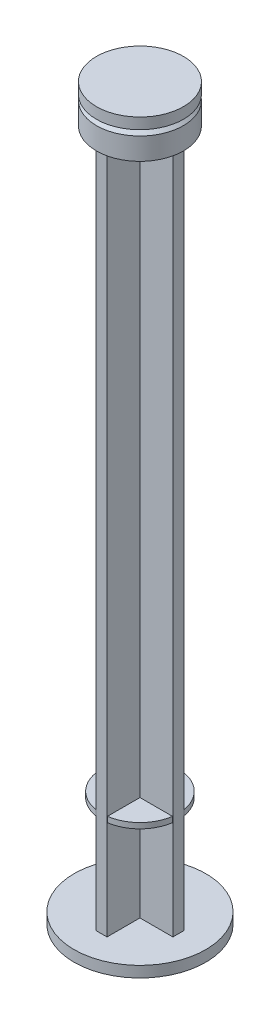
SolidWorks part; units mm, degrees
ref_plane "Front Plane" through (0, 0, 0) normal (0, 0, 1) x (1, 0, 0)
ref_plane "Top Plane" through (0, 0, 0) normal (0, 1, 0) x (1, 0, 0)
ref_plane "Right Plane" through (0, 0, 0) normal (1, 0, 0) x (0, 0, -1)
sketch "Sketch1" plane through (0, 0, 0) normal (0, 1, 0) x (1, 0, 0)
  circle A0 centre (0, 0) radius 6
  dimension "D1" = 12
extrude "Extrude1" add sketch "Sketch1" along normal blind 1
sketch "Sketch2" plane through (0, 1, 0) normal (0, 1, 0) x (-1, 0, 0)
  line L0 (0.5, 0.5) -> (0.5, 3.5)
  line L1 (-3.5, -0.5) -> (-0.5, -0.5)
  line L2 (-3.5, -0.5) -> (-3.5, 0.5)
  line L3 (-3.5, 0.5) -> (-0.5, 0.5)
  line L4 (3.5, -0.5) -> (3.5, 0.5)
  line L5 (-0.5, -3.5) -> (0.5, -3.5)
  line L6 (-0.5, -3.5) -> (-0.5, -0.5)
  line L7 (-0.5, 3.5) -> (0.5, 3.5)
  line L8 (0.5, -3.5) -> (0.5, -0.5)
  line L9 (0.5, 0.5) -> (3.5, 0.5)
  line L10 (-0.5, 0.5) -> (-0.5, 3.5)
  line L11 (0.5, -0.5) -> (3.5, -0.5)
  dimension "D1" = 0.5
  dimension "D2" = 0.5
  dimension "D3" = 3.5
  dimension "D4" = 3.5
  dimension "D5" = 0.5
  dimension "D6" = 0.5
  dimension "D7" = 3.5
  dimension "D8" = 3.5
extrude "Extrude2" add sketch "Sketch2" along normal blind 62
ref_plane "Plane1" through (0, 10, 0) normal (0, 1, 0) x (-1, 0, 0)
sketch "Sketch5" plane through (0, 10, 0) normal (0, 1, 0) x (-1, 0, 0)
  circle A0 centre (0, 0) radius 3.5
extrude "Extrude4" add sketch "Sketch5" along normal blind 0.5
sketch "Sketch6" plane through (0, 63, 0) normal (0, 1, 0) x (-1, 0, 0)
  circle A0 centre (0, 0) radius 0.5338
extrude "Extrude5" add sketch "Sketch6" along normal blind 1.5
sketch "Sketch7" plane through (0, 63, 0) normal (0, 1, 0) x (-1, 0, 0)
  circle A0 centre (0, 0) radius 3.9625
extrude "Extrude6" add sketch "Sketch7" along normal blind 2.5
chamfer "Chamfer1" distance 0.5 angle 45 1 edges at (0, 65.5, 3.9625)
sketch "Sketch8" plane through (0, 65.5, 0) normal (0, 1, 0) x (-1, 0, 0)
  circle A0 centre (0, 0) radius 3.965
extrude "Extrude7" add sketch "Sketch8" along normal blind 1
